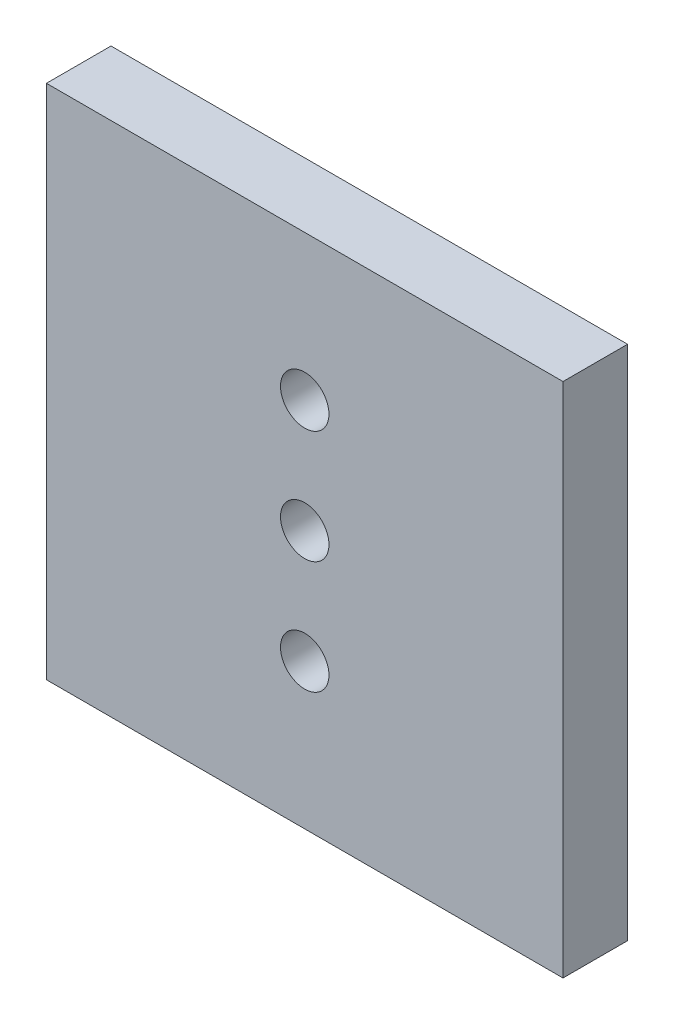
SolidWorks part; units mm, degrees
ref_plane "Front Plane" through (0, 0, 0) normal (0, 0, 1) x (1, 0, 0)
ref_plane "Top Plane" through (0, 0, 0) normal (0, 1, 0) x (1, 0, 0)
ref_plane "Right Plane" through (0, 0, 0) normal (1, 0, 0) x (0, 0, -1)
ref_plane "Plane1" through (0, 0, 300) normal (0, 0, 1) x (1, 0, 0)
sketch "Sketch1" plane through (0, 0, 300) normal (0, 0, 1) x (1, 0, 0)
  line L1 (268, 268) -> (332, 268)
  line L2 (268, 268) -> (268, 332)
  line L3 (268, 332) -> (332, 332)
  line L4 (332, 268) -> (332, 332)
extrude "Boss-Extrude1" add sketch "Sketch1" along normal blind 8
sketch "Sketch2" plane through (0, 0, 308) normal (0, 0, 1) x (1, 0, 0)
  circle A0 centre (300, 300) radius 3
extrude "Cut-Extrude1" cut sketch "Sketch2" against normal blind 28
sketch "Sketch3" plane through (0, 0, 308) normal (0, 0, 1) x (1, 0, 0)
  circle A0 centre (300, 314) radius 3
extrude "Cut-Extrude2" cut sketch "Sketch3" against normal blind 28
sketch "Sketch4" plane through (0, 0, 308) normal (0, 0, 1) x (1, 0, 0)
  circle A0 centre (300, 286) radius 3
extrude "Cut-Extrude3" cut sketch "Sketch4" against normal blind 28
